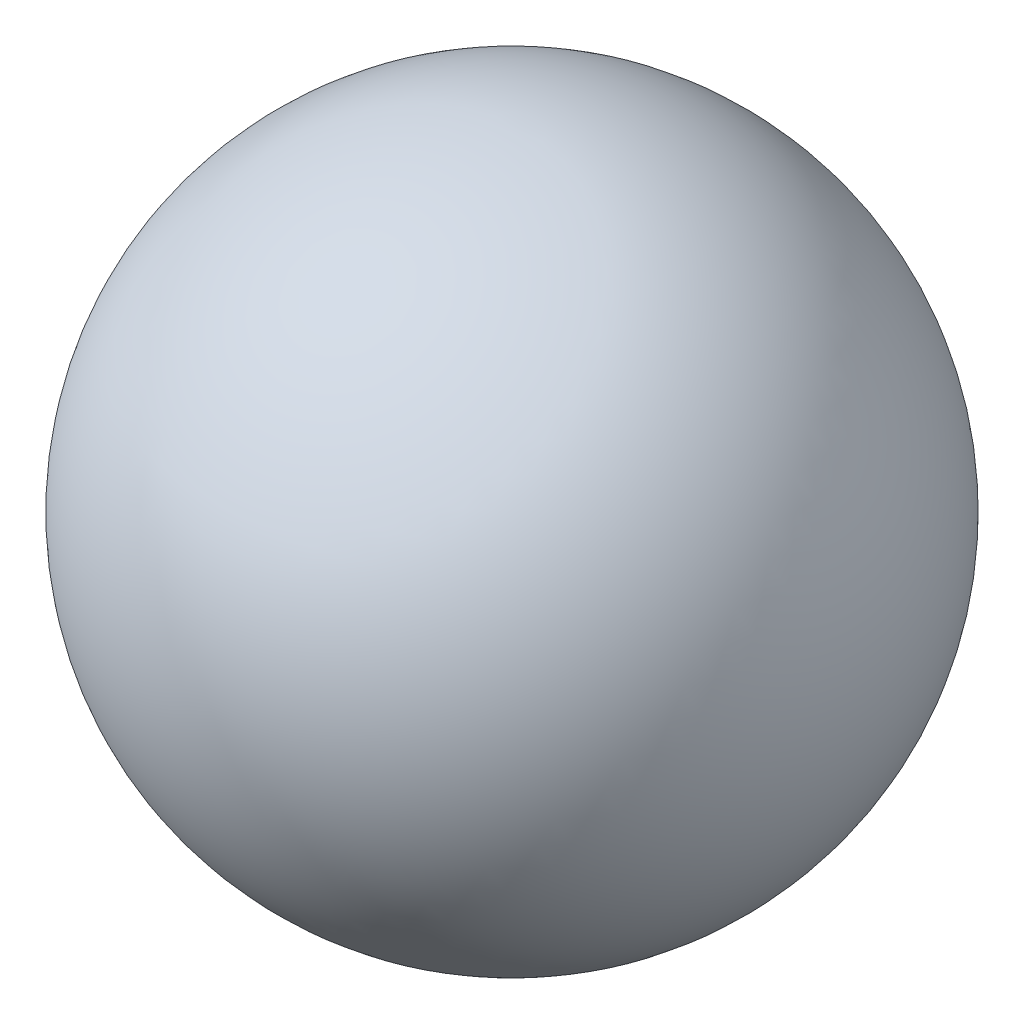
SolidWorks part; units mm, degrees
material "PVC 0.007 Plasticizado"
ref_plane "Plano frontal" through (0, 0, 0) normal (0, 0, 1) x (1, 0, 0)
ref_plane "Plano superior" through (0, 0, 0) normal (0, 1, 0) x (1, 0, 0)
ref_plane "Plano direito" through (0, 0, 0) normal (1, 0, 0) x (0, 0, -1)
sketch "Esboço2" plane through (0, 0, 0) normal (0, 0, 1) x (1, 0, 0)
  line L0 (0, 0) -> (0, 50)
  arc A0 (0, 0) -> (0, 50) centre (0, 25) ccw
  dimension "D1" = 50
revolve "Revolução1" add sketch "Esboço2" angle 360 about L0
